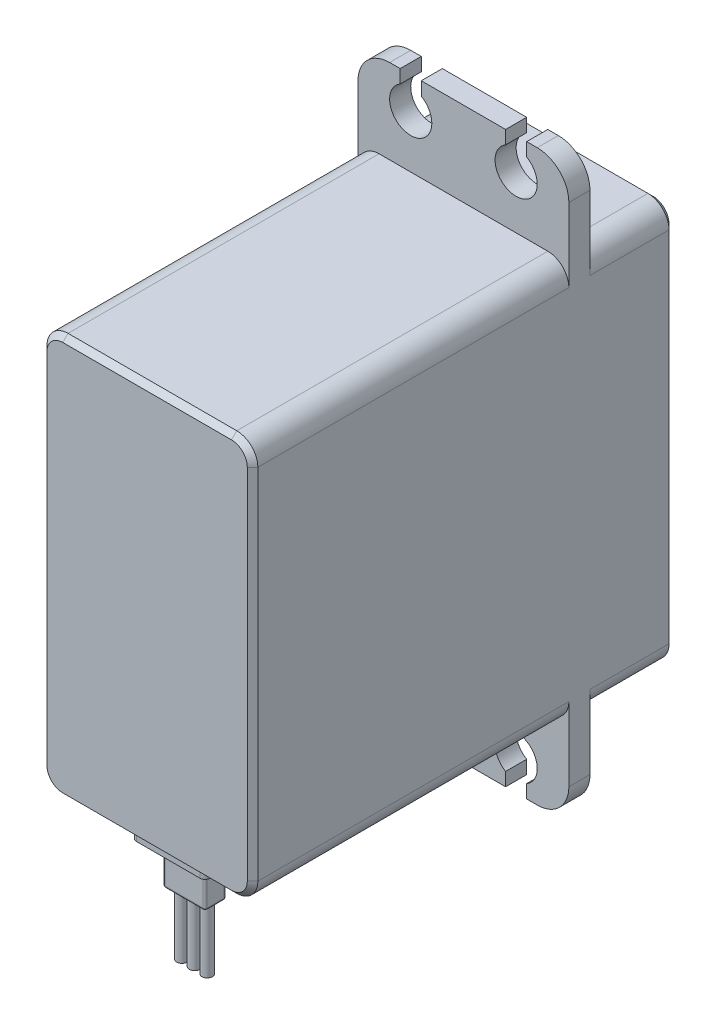
SolidWorks part; units mm, degrees
ref_plane "前视基准面" through (0, 0, 0) normal (0, 0, 1) x (1, 0, 0)
ref_plane "上视基准面" through (0, 0, 0) normal (0, 1, 0) x (1, 0, 0)
ref_plane "右视基准面" through (0, 0, 0) normal (1, 0, 0) x (0, 0, -1)
sketch "草图1" plane through (0, 0, 0) normal (0, 0, 1) x (1, 0, 0)
  line L1 (-10, -27) -> (10, -27)
  line L2 (-10, -27) -> (-10, 27)
  line L3 (-10, 27) -> (10, 27)
  line L4 (10, -27) -> (10, 27)
  line L5 (-10, -27) -> (10, 27) construction
  line L6 (-10, 27) -> (10, -27) construction
  point P0 (0, 0)
  dimension "D1" = 20
  dimension "D2" = 54
extrude "凸台-拉伸1" add sketch "草图1" along normal blind 40
sketch "草图2" plane through (0, 0, 40) normal (0, 0, 1) x (1, 0, 0)
  line L0 (10, -27) -> (10, 27) construction
  line L1 (-10, -19) -> (10, -19)
  line L2 (-10, -19) -> (-10, 19)
  line L3 (-10, 19) -> (10, 19)
  line L4 (10, -19) -> (10, 19)
  line L5 (-10, -19) -> (10, 19) construction
  line L6 (-10, 19) -> (10, -19) construction
  point P0 (0, 0)
  dimension "D1" = 38
extrude "切除-拉伸1" cut sketch "草图2" against normal blind 30 flip side to cut
sketch "草图3" plane through (0, 0, 0) normal (0, 0, -1) x (-1, 0, 0)
  line L0 (10, 27) -> (10, -27) construction
  line L1 (-10, -19) -> (10, -19)
  line L2 (-10, -19) -> (-10, 19)
  line L3 (-10, 19) -> (10, 19)
  line L4 (10, -19) -> (10, 19)
  line L5 (-10, -19) -> (10, 19) construction
  line L6 (-10, 19) -> (10, -19) construction
  point P0 (0, 0)
  dimension "D1" = 38
extrude "切除-拉伸2" cut sketch "草图3" against normal blind 8 flip side to cut
sketch "草图4" plane through (0, 0, 10) normal (0, 0, 1) x (1, 0, 0)
  line L0 (4, 25.7321) -> (4, 27)
  line L1 (10, 27) -> (-10, 27) construction
  line L2 (4, 27) -> (6, 27)
  line L3 (6, 27) -> (6, 25.7321)
  line L4 (5, 24) -> (5, 27) construction
  line L5 (10, 19) -> (10, 27) construction
  line L6 (-6, 25.7321) -> (-6, 27)
  line L7 (-4, 27) -> (-4, 25.7321)
  line L8 (-6, 27) -> (-4, 27)
  arc A0 (4, 25.7321) -> (6, 25.7321) centre (5, 24) ccw
  arc A1 (-6, 25.7321) -> (-4, 25.7321) centre (-5, 24) ccw
  dimension "D1" = 2
  dimension "D2" = 3
  dimension "D3" = 2
  dimension "D4" = 4
  dimension "D6" = 10
  dimension "D5" = 2
extrude "切除-拉伸3" cut sketch "草图4" against normal through all
mirror "镜向1" about plane through (0, 0, 0) normal (0, 1, 0) of "切除-拉伸3"
sketch "草图6" plane through (0, -19, 0) normal (0, -1, 0) x (1, 0, 0)
  line L0 (0, 0) -> (0, 40) construction
  line L1 (-10, 40) -> (10, 40) construction
  line L3 (3.5, 38) -> (-3.5, 38)
  line L4 (3.5, 38) -> (3.5, 33)
  line L5 (3.5, 33) -> (-3.5, 33)
  line L6 (-3.5, 38) -> (-3.5, 33)
  line L7 (3.5, 38) -> (-3.5, 33) construction
  line L8 (3.5, 33) -> (-3.5, 38) construction
  point P5 (0, 35.5)
  dimension "D1" = 7
  dimension "D2" = 5
  dimension "D3" = 2
extrude "凸台-拉伸2" add sketch "草图6" along normal blind 2
sketch "草图7" plane through (0, -21, 0) normal (0, -1, 0) x (1, 0, 0)
  line L0 (-3.5, 38) -> (3.5, 33) construction
  line L1 (-2, 34.5) -> (2, 34.5)
  line L2 (-2, 34.5) -> (-2, 36.5)
  line L3 (-2, 36.5) -> (2, 36.5)
  line L4 (2, 34.5) -> (2, 36.5)
  line L5 (-2, 34.5) -> (2, 36.5) construction
  line L6 (-2, 36.5) -> (2, 34.5) construction
  line L7 (-3.5, 38) -> (-3.5, 33) construction
  line L8 (3.5, 38) -> (-3.5, 38) construction
  line L9 (3.5, 38) -> (-3.5, 33) construction
  point P0 (0, 35.5)
  dimension "D1" = 4
  dimension "D2" = 2
extrude "凸台-拉伸3" add sketch "草图7" along normal blind 4
sketch "草图8" plane through (0, -25, 0) normal (0, -1, 0) x (1, 0, 0)
  line L0 (2, 34.5) -> (2, 36.5) construction
  line L1 (-2, 35.5) -> (2, 35.5) construction
  line L2 (-2, 36.5) -> (-2, 34.5) construction
  circle A0 centre (1.2, 35.5) radius 0.5
  circle A1 centre (0, 35.5) radius 0.5
  circle A2 centre (-1.2, 35.5) radius 0.5
  dimension "D1" = 1
  dimension "D2" = 0.8
  dimension "D3" = 1.2
  dimension "D4" = 1.2
extrude "凸台-拉伸4" add sketch "草图8" along normal blind 6
sketch "草图9" plane through (0, 0, 0) normal (0, 0, -1) x (-1, 0, 0)
  line L0 (-10, -19) -> (10, -19) construction
  circle A0 centre (0, -9) radius 6.5
  dimension "D1" = 10
  dimension "D2" = 13
extrude "凸台-拉伸5" add sketch "草图9" along normal blind 2
sketch "草图10" plane through (0, 0, -2) normal (0, 0, -1) x (-1, 0, 0)
  circle A0 centre (0, -9) radius 5
  dimension "D1" = 10
extrude "切除-拉伸4" cut sketch "草图10" against normal blind 0.8
sketch "草图11" plane through (0, 0, -1.2) normal (0, 0, -1) x (-1, 0, 0)
  circle A0 centre (0, -9) radius 2.5
  dimension "D1" = 5
extrude "切除-拉伸5" cut sketch "草图11" against normal blind 4
sketch "草图12" plane through (0, 0, 2.8) normal (0, 0, -1) x (-1, 0, 0)
  circle A0 centre (0, -9) radius 2.5 construction
  circle A1 centre (0, -9) radius 2.5
extrude "凸台-拉伸6" add sketch "草图12" along normal blind 10 separate body
sketch "草图13" plane through (0, 0, -7.2) normal (0, 0, -1) x (-1, 0, 0)
  line L0 (0, -9) -> (0, -6.5) construction
  line L1 (-0.2796, -6.5157) -> (0, -7)
  line L2 (0, -7) -> (0.2796, -6.5157)
  line L3 (0.5018, -6.5509) -> (0.618, -7.0979)
  line L4 (0.618, -7.0979) -> (1.0336, -6.7237)
  line L5 (1.234, -6.8258) -> (1.1756, -7.382)
  line L6 (1.1756, -7.382) -> (1.6865, -7.1545)
  line L7 (1.8455, -7.3135) -> (1.618, -7.8244)
  line L8 (1.618, -7.8244) -> (2.1742, -7.766)
  line L9 (2.2763, -7.9664) -> (1.9021, -8.382)
  line L10 (1.9021, -8.382) -> (2.4491, -8.4982)
  line L11 (2.4843, -8.7204) -> (2, -9)
  line L12 (2, -9) -> (2.4843, -9.2796)
  line L13 (2.4491, -9.5018) -> (1.9021, -9.618)
  line L14 (1.9021, -9.618) -> (2.2763, -10.0336)
  line L15 (2.1742, -10.234) -> (1.618, -10.1756)
  line L16 (1.618, -10.1756) -> (1.8455, -10.6865)
  line L17 (1.6865, -10.8455) -> (1.1756, -10.618)
  line L18 (1.1756, -10.618) -> (1.234, -11.1742)
  line L19 (1.0336, -11.2763) -> (0.618, -10.9021)
  line L20 (0.618, -10.9021) -> (0.5018, -11.4491)
  line L21 (0.2796, -11.4843) -> (0, -11)
  line L22 (0, -11) -> (-0.2796, -11.4843)
  line L23 (-0.5018, -11.4491) -> (-0.618, -10.9021)
  line L24 (-0.618, -10.9021) -> (-1.0336, -11.2763)
  line L25 (-1.234, -11.1742) -> (-1.1756, -10.618)
  line L26 (-1.1756, -10.618) -> (-1.6865, -10.8455)
  line L27 (-1.8455, -10.6865) -> (-1.618, -10.1756)
  line L28 (-1.618, -10.1756) -> (-2.1742, -10.234)
  line L29 (-2.2763, -10.0336) -> (-1.9021, -9.618)
  line L30 (-1.9021, -9.618) -> (-2.4491, -9.5018)
  line L31 (-2.4843, -9.2796) -> (-2, -9)
  line L32 (-2, -9) -> (-2.4843, -8.7204)
  line L33 (-2.4491, -8.4982) -> (-1.9021, -8.382)
  line L34 (-1.9021, -8.382) -> (-2.2763, -7.9664)
  line L35 (-2.1742, -7.766) -> (-1.618, -7.8244)
  line L36 (-1.618, -7.8244) -> (-1.8455, -7.3135)
  line L37 (-1.6865, -7.1545) -> (-1.1756, -7.382)
  line L38 (-1.1756, -7.382) -> (-1.234, -6.8258)
  line L39 (-1.0336, -6.7237) -> (-0.618, -7.0979)
  line L40 (-0.618, -7.0979) -> (-0.5018, -6.5509)
  circle A0 centre (0, -9) radius 2.5 construction
  circle A1 centre (0, -9) radius 2.5 construction
  arc A2 (0.2796, -6.5157) -> (-0.2796, -6.5157) centre (0, -9) ccw
  arc A3 (1.0336, -6.7237) -> (0.5018, -6.5509) centre (0, -9) ccw
  arc A4 (1.6865, -7.1545) -> (1.234, -6.8258) centre (0, -9) ccw
  arc A5 (2.1742, -7.766) -> (1.8455, -7.3135) centre (0, -9) ccw
  arc A6 (2.4491, -8.4982) -> (2.2763, -7.9664) centre (0, -9) ccw
  arc A7 (2.4843, -9.2796) -> (2.4843, -8.7204) centre (0, -9) ccw
  arc A8 (2.2763, -10.0336) -> (2.4491, -9.5018) centre (0, -9) ccw
  arc A9 (1.8455, -10.6865) -> (2.1742, -10.234) centre (0, -9) ccw
  arc A10 (1.234, -11.1742) -> (1.6865, -10.8455) centre (0, -9) ccw
  arc A11 (0.5018, -11.4491) -> (1.0336, -11.2763) centre (0, -9) ccw
  arc A12 (-0.2796, -11.4843) -> (0.2796, -11.4843) centre (0, -9) ccw
  arc A13 (-1.0336, -11.2763) -> (-0.5018, -11.4491) centre (0, -9) ccw
  arc A14 (-1.6865, -10.8455) -> (-1.234, -11.1742) centre (0, -9) ccw
  arc A15 (-2.1742, -10.234) -> (-1.8455, -10.6865) centre (0, -9) ccw
  arc A16 (-2.4491, -9.5018) -> (-2.2763, -10.0336) centre (0, -9) ccw
  arc A17 (-2.4843, -8.7204) -> (-2.4843, -9.2796) centre (0, -9) ccw
  arc A18 (-2.2763, -7.9664) -> (-2.4491, -8.4982) centre (0, -9) ccw
  arc A19 (-1.8455, -7.3135) -> (-2.1742, -7.766) centre (0, -9) ccw
  arc A20 (-1.234, -6.8258) -> (-1.6865, -7.1545) centre (0, -9) ccw
  arc A21 (-0.5018, -6.5509) -> (-1.0336, -6.7237) centre (0, -9) ccw
  point P70 (0, -9)
  dimension "D1" = 2
  dimension "D2" = 60
  dimension "D3" = 20
extrude "切除-拉伸6" cut sketch "草图13" against normal through all
sketch "草图14" plane through (0, 0, 0) normal (1, 0, 0) x (0, 0, -1)
  line L0 (7.2, -7) -> (7.2, -6)
  line L1 (7.2, -7.382) -> (7.2, -6.8258) construction
  line L2 (7.2, -6) -> (6.6226, -6)
  line L3 (6.6226, -6) -> (7.2, -7)
  dimension "D1" = 30
  dimension "D2" = 1
revolve "切除-旋转1" cut sketch "草图14" angle 360 about axis through (0, -9, -7.2) along (0, 0, 1)
ref_plane "基准面1" through (0, 0, -2.2) normal (0, 0, 1) x (1, 0, 0)
mirror "镜向2" about plane through (0, 0, -2.2) normal (0, 0, 1) of "切除-旋转1"
fillet "圆角1" radius 2 8 edges at (-10, -19, 4) (-10, -19, 25) (10, -19, 4) (10, -19, 25) (-10, 19, 4) (-10, 19, 25) (10, 19, 4) (10, 19, 25)
chamfer "倒角1" distance 0.5 angle 45 17 edges at (0, 19, 0) (-10, 0, 0) (0, -19, 0) (10, 0, 0) (-10, 0, 40) (0, -19, 40) (10, 0, 40) (0, 19, 40) (-9.4142, -18.4142, 0) (-9.4142, 18.4142, 0) (9.4142, -18.4142, 0) (9.4142, 18.4142, 0) (9.4142, -18.4142, 40) (-9.4142, -18.4142, 40) (9.4142, 18.4142, 40) (-9.4142, 18.4142, 40) (-6.5, -9, -2)
fillet "圆角2" radius 3 4 edges at (10, -27, 9) (-10, -27, 9) (-10, 27, 9) (10, 27, 9)
fillet "圆角3" radius 0.5 4 edges at (-3.5, -20, 38) (3.5, -20, 33) (-3.5, -20, 33) (3.5, -20, 38)
fillet "圆角4" radius 0.2 8 edges at (2, -23, 34.5) (-2, -23, 34.5) (-2, -23, 36.5) (2, -23, 36.5) (0, -25, 34.5) (-2, -25, 35.5) (0, -25, 36.5) (2, -25, 35.5)
hole_wizard "M2 螺纹孔2" positions "3D草图3" profile "草图17" tap size "M2" standard "GB"
sketch3d "3D草图3"
  arc A0 (0.618, -7.0979, -7.2) -> (1.1756, -7.382, -7.2) centre (0, -9, -7.2) ccw construction
  point P0 (0, -9, -7.2)
  point P7 (0, -9, -9.2)
sketch "草图17" plane through (0, -9, -7.2) normal (1, 0, 0) x (0, 1, 0)
  line L0 (0, 0) -> (0, 10.4807)
  line L1 (0, 10.4807) -> (0.8, 10)
  line L2 (0.8, 10) -> (0.8, 0)
  line L5 (0.8, 0) -> (0, 0)
  line L10 (0, 10.4807) -> (-0.8, 10) construction
  line L11 (0, -6.35) -> (0, 107.95) construction
  dimension "螺纹孔钻头直径" = 1.6
  dimension "螺纹孔钻头深度" = 10
  dimension "导头角度" = 118
cosmetic thread "孔螺蚊线10" parameters "D1"=4, "D2"=2
move or copy body "实体-移动/复制1" [suppressed] bodies to move or copy 123 124
